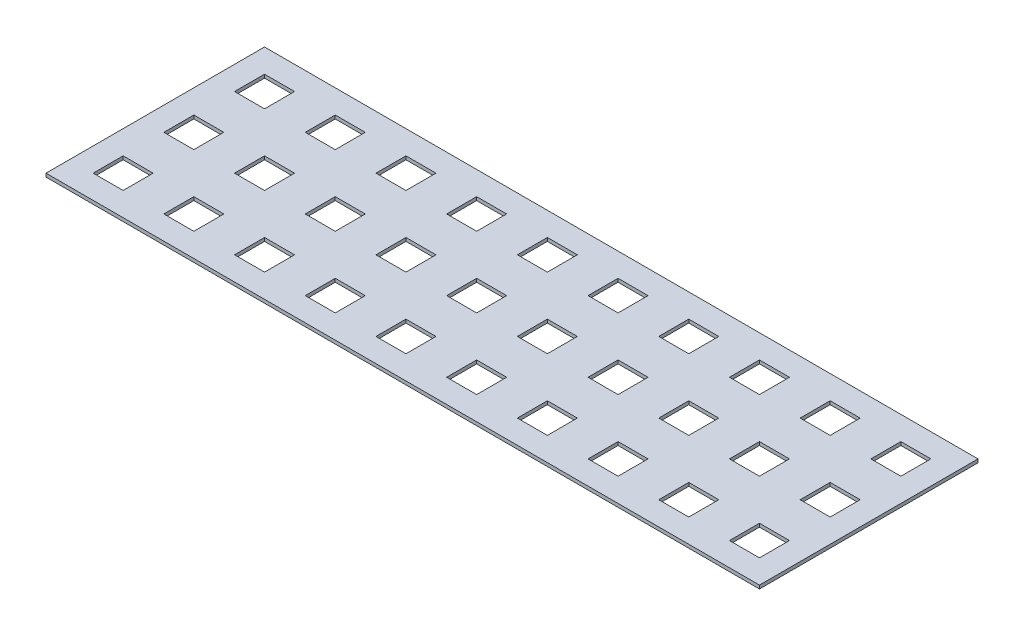
SolidWorks part; units mm, degrees
ref_plane "Ön Düzlem" through (0, 0, 0) normal (0, 0, 1) x (1, 0, 0)
ref_plane "Üst Düzlem" through (0, 0, 0) normal (0, 1, 0) x (1, 0, 0)
ref_plane "Sağ Düzlem" through (0, 0, 0) normal (1, 0, 0) x (0, 0, -1)
sketch "Çizim1" plane through (0, 0, 0) normal (0, 1, 0) x (1, 0, 0)
  line L0 (18, 49.5) -> (18, 34.5) construction
  line L1 (0, 0) -> (166.5, 0)
  line L2 (0, 0) -> (0, 51)
  line L3 (0, 51) -> (166.5, 51)
  line L4 (166.5, 0) -> (166.5, 51)
  line L5 (1.5, 49.5) -> (16.5, 49.5) construction
  line L6 (1.5, 49.5) -> (1.5, 34.5) construction
  line L7 (1.5, 34.5) -> (16.5, 34.5) construction
  line L8 (16.5, 49.5) -> (16.5, 34.5) construction
  line L9 (18, 49.5) -> (33, 49.5) construction
  line L10 (33, 49.5) -> (33, 34.5) construction
  line L11 (18, 34.5) -> (33, 34.5) construction
  line L12 (34.5, 49.5) -> (34.5, 34.5) construction
  line L13 (34.5, 49.5) -> (49.5, 49.5) construction
  line L14 (49.5, 49.5) -> (49.5, 34.5) construction
  line L15 (34.5, 34.5) -> (49.5, 34.5) construction
  line L16 (51, 49.5) -> (51, 34.5) construction
  line L17 (51, 49.5) -> (66, 49.5) construction
  line L18 (66, 49.5) -> (66, 34.5) construction
  line L19 (51, 34.5) -> (66, 34.5) construction
  line L20 (67.5, 49.5) -> (67.5, 34.5) construction
  line L21 (67.5, 49.5) -> (82.5, 49.5) construction
  line L22 (82.5, 49.5) -> (82.5, 34.5) construction
  line L23 (67.5, 34.5) -> (82.5, 34.5) construction
  line L24 (84, 49.5) -> (84, 34.5) construction
  line L25 (84, 49.5) -> (99, 49.5) construction
  line L26 (99, 49.5) -> (99, 34.5) construction
  line L27 (84, 34.5) -> (99, 34.5) construction
  line L28 (100.5, 49.5) -> (100.5, 34.5) construction
  line L29 (100.5, 49.5) -> (115.5, 49.5) construction
  line L30 (115.5, 49.5) -> (115.5, 34.5) construction
  line L31 (100.5, 34.5) -> (115.5, 34.5) construction
  line L32 (117, 49.5) -> (117, 34.5) construction
  line L33 (117, 49.5) -> (132, 49.5) construction
  line L34 (132, 49.5) -> (132, 34.5) construction
  line L35 (117, 34.5) -> (132, 34.5) construction
  line L36 (133.5, 49.5) -> (133.5, 34.5) construction
  line L37 (133.5, 49.5) -> (148.5, 49.5) construction
  line L38 (148.5, 49.5) -> (148.5, 34.5) construction
  line L39 (133.5, 34.5) -> (148.5, 34.5) construction
  line L40 (150, 49.5) -> (150, 34.5) construction
  line L41 (150, 49.5) -> (165, 49.5) construction
  line L42 (165, 49.5) -> (165, 34.5) construction
  line L43 (150, 34.5) -> (165, 34.5) construction
  line L44 (1.5, 33) -> (1.5, 18) construction
  line L45 (1.5, 33) -> (16.5, 33) construction
  line L46 (16.5, 33) -> (16.5, 18) construction
  line L47 (1.5, 18) -> (16.5, 18) construction
  line L48 (18, 33) -> (33, 33) construction
  line L49 (18, 33) -> (18, 18) construction
  line L50 (18, 18) -> (33, 18) construction
  line L51 (33, 33) -> (33, 18) construction
  line L52 (34.5, 33) -> (34.5, 18) construction
  line L53 (34.5, 33) -> (49.5, 33) construction
  line L54 (34.5, 18) -> (49.5, 18) construction
  line L55 (49.5, 33) -> (49.5, 18) construction
  line L56 (51, 33) -> (51, 18) construction
  line L57 (51, 33) -> (66, 33) construction
  line L58 (51, 18) -> (66, 18) construction
  line L59 (66, 33) -> (66, 18) construction
  line L60 (67.5, 33) -> (67.5, 18) construction
  line L61 (67.5, 33) -> (82.5, 33) construction
  line L62 (67.5, 18) -> (82.5, 18) construction
  line L63 (82.5, 33) -> (82.5, 18) construction
  line L64 (84, 33) -> (84, 18) construction
  line L65 (84, 33) -> (99, 33) construction
  line L66 (84, 18) -> (99, 18) construction
  line L67 (99, 33) -> (99, 18) construction
  line L68 (100.5, 33) -> (100.5, 18) construction
  line L69 (100.5, 18) -> (115.5, 18) construction
  line L70 (115.5, 33) -> (115.5, 18) construction
  line L71 (117, 33) -> (117, 18) construction
  line L72 (100.5, 33) -> (115.5, 33) construction
  line L73 (117, 33) -> (132, 33) construction
  line L74 (117, 18) -> (132, 18) construction
  line L75 (132, 33) -> (132, 18) construction
  line L76 (133.5, 33) -> (133.5, 18) construction
  line L77 (133.5, 18) -> (148.5, 18) construction
  line L78 (150, 18) -> (165, 18) construction
  line L79 (150, 33) -> (150, 18) construction
  line L80 (148.5, 33) -> (148.5, 18) construction
  line L81 (165, 33) -> (165, 18) construction
  line L82 (150, 33) -> (165, 33) construction
  line L83 (133.5, 33) -> (148.5, 33) construction
  line L84 (1.5, 16.5) -> (1.5, 1.5) construction
  line L85 (1.5, 16.5) -> (16.5, 16.5) construction
  line L86 (16.5, 16.5) -> (16.5, 1.5) construction
  line L87 (1.5, 1.5) -> (16.5, 1.5) construction
  line L88 (18, 16.5) -> (33, 16.5) construction
  line L89 (18, 16.5) -> (18, 1.5) construction
  line L90 (18, 1.5) -> (33, 1.5) construction
  line L91 (33, 16.5) -> (33, 1.5) construction
  line L92 (34.5, 16.5) -> (34.5, 1.5) construction
  line L93 (34.5, 16.5) -> (49.5, 16.5) construction
  line L94 (34.5, 1.5) -> (49.5, 1.5) construction
  line L95 (49.5, 16.5) -> (49.5, 1.5) construction
  line L96 (51, 16.5) -> (51, 1.5) construction
  line L97 (51, 16.5) -> (66, 16.5) construction
  line L98 (51, 1.5) -> (66, 1.5) construction
  line L99 (66, 16.5) -> (66, 1.5) construction
  line L100 (67.5, 16.5) -> (67.5, 1.5) construction
  line L101 (67.5, 16.5) -> (82.5, 16.5) construction
  line L102 (67.5, 1.5) -> (82.5, 1.5) construction
  line L103 (82.5, 16.5) -> (82.5, 1.5) construction
  line L104 (84, 16.5) -> (84, 1.5) construction
  line L105 (84, 16.5) -> (99, 16.5) construction
  line L106 (84, 1.5) -> (99, 1.5) construction
  line L107 (99, 16.5) -> (99, 1.5) construction
  line L108 (100.5, 16.5) -> (100.5, 1.5) construction
  line L109 (100.5, 1.5) -> (115.5, 1.5) construction
  line L110 (115.5, 16.5) -> (115.5, 1.5) construction
  line L111 (117, 16.5) -> (117, 1.5) construction
  line L112 (100.5, 16.5) -> (115.5, 16.5) construction
  line L113 (117, 16.5) -> (132, 16.5) construction
  line L114 (117, 1.5) -> (132, 1.5) construction
  line L115 (132, 16.5) -> (132, 1.5) construction
  line L116 (133.5, 16.5) -> (133.5, 1.5) construction
  line L117 (133.5, 1.5) -> (148.5, 1.5) construction
  line L118 (150, 1.5) -> (165, 1.5) construction
  line L119 (150, 16.5) -> (150, 1.5) construction
  line L120 (148.5, 16.5) -> (148.5, 1.5) construction
  line L121 (165, 16.5) -> (165, 1.5) construction
  line L122 (150, 16.5) -> (165, 16.5) construction
  line L123 (133.5, 16.5) -> (148.5, 16.5) construction
  line L124 (16.5, 49.5) -> (1.5, 34.5) construction
  line L125 (1.5, 49.5) -> (16.5, 34.5) construction
  line L126 (18, 49.5) -> (33, 34.5) construction
  line L127 (33, 49.5) -> (18, 34.5) construction
  line L128 (22, 45.5) -> (22, 38.5)
  line L129 (5.5, 45.5) -> (12.5, 45.5)
  line L130 (5.5, 45.5) -> (5.5, 38.5)
  line L131 (5.5, 38.5) -> (12.5, 38.5)
  line L132 (12.5, 45.5) -> (12.5, 38.5)
  line L133 (5.5, 45.5) -> (12.5, 38.5) construction
  line L134 (5.5, 38.5) -> (12.5, 45.5) construction
  line L135 (22, 45.5) -> (29, 45.5)
  line L136 (29, 45.5) -> (29, 38.5)
  line L137 (22, 38.5) -> (29, 38.5)
  line L138 (38.5, 45.5) -> (38.5, 38.5)
  line L139 (38.5, 45.5) -> (45.5, 45.5)
  line L140 (45.5, 45.5) -> (45.5, 38.5)
  line L141 (38.5, 38.5) -> (45.5, 38.5)
  line L142 (55, 45.5) -> (55, 38.5)
  line L143 (55, 45.5) -> (62, 45.5)
  line L144 (62, 45.5) -> (62, 38.5)
  line L145 (55, 38.5) -> (62, 38.5)
  line L146 (71.5, 45.5) -> (71.5, 38.5)
  line L147 (71.5, 45.5) -> (78.5, 45.5)
  line L148 (78.5, 45.5) -> (78.5, 38.5)
  line L149 (71.5, 38.5) -> (78.5, 38.5)
  line L150 (88, 45.5) -> (88, 38.5)
  line L151 (88, 45.5) -> (95, 45.5)
  line L152 (95, 45.5) -> (95, 38.5)
  line L153 (88, 38.5) -> (95, 38.5)
  line L154 (104.5, 45.5) -> (104.5, 38.5)
  line L155 (104.5, 45.5) -> (111.5, 45.5)
  line L156 (111.5, 45.5) -> (111.5, 38.5)
  line L157 (104.5, 38.5) -> (111.5, 38.5)
  line L158 (121, 45.5) -> (121, 38.5)
  line L159 (121, 45.5) -> (128, 45.5)
  line L160 (128, 45.5) -> (128, 38.5)
  line L161 (121, 38.5) -> (128, 38.5)
  line L162 (137.5, 45.5) -> (137.5, 38.5)
  line L163 (137.5, 45.5) -> (144.5, 45.5)
  line L164 (144.5, 45.5) -> (144.5, 38.5)
  line L165 (137.5, 38.5) -> (144.5, 38.5)
  line L166 (154, 45.5) -> (154, 38.5)
  line L167 (154, 45.5) -> (161, 45.5)
  line L168 (161, 45.5) -> (161, 38.5)
  line L169 (154, 38.5) -> (161, 38.5)
  line L170 (22, 29) -> (22, 22)
  line L171 (22, 29) -> (29, 29)
  line L172 (29, 29) -> (29, 22)
  line L173 (22, 22) -> (29, 22)
  line L174 (38.5, 29) -> (38.5, 22)
  line L175 (38.5, 29) -> (45.5, 29)
  line L176 (45.5, 29) -> (45.5, 22)
  line L177 (38.5, 22) -> (45.5, 22)
  line L178 (55, 29) -> (55, 22)
  line L179 (55, 29) -> (62, 29)
  line L180 (62, 29) -> (62, 22)
  line L181 (55, 22) -> (62, 22)
  line L182 (71.5, 29) -> (71.5, 22)
  line L183 (71.5, 29) -> (78.5, 29)
  line L184 (78.5, 29) -> (78.5, 22)
  line L185 (71.5, 22) -> (78.5, 22)
  line L186 (88, 29) -> (88, 22)
  line L187 (88, 29) -> (95, 29)
  line L188 (95, 29) -> (95, 22)
  line L189 (88, 22) -> (95, 22)
  line L190 (104.5, 29) -> (104.5, 22)
  line L191 (104.5, 29) -> (111.5, 29)
  line L192 (111.5, 29) -> (111.5, 22)
  line L193 (104.5, 22) -> (111.5, 22)
  line L194 (121, 29) -> (121, 22)
  line L195 (121, 29) -> (128, 29)
  line L196 (128, 29) -> (128, 22)
  line L197 (121, 22) -> (128, 22)
  line L198 (137.5, 29) -> (137.5, 22)
  line L199 (137.5, 29) -> (144.5, 29)
  line L200 (144.5, 29) -> (144.5, 22)
  line L201 (137.5, 22) -> (144.5, 22)
  line L202 (154, 29) -> (154, 22)
  line L203 (154, 29) -> (161, 29)
  line L204 (161, 29) -> (161, 22)
  line L205 (154, 22) -> (161, 22)
  line L206 (22, 12.5) -> (22, 5.5)
  line L207 (22, 12.5) -> (29, 12.5)
  line L208 (29, 12.5) -> (29, 5.5)
  line L209 (22, 5.5) -> (29, 5.5)
  line L210 (38.5, 12.5) -> (38.5, 5.5)
  line L211 (38.5, 12.5) -> (45.5, 12.5)
  line L212 (45.5, 12.5) -> (45.5, 5.5)
  line L213 (38.5, 5.5) -> (45.5, 5.5)
  line L214 (55, 12.5) -> (55, 5.5)
  line L215 (55, 12.5) -> (62, 12.5)
  line L216 (62, 12.5) -> (62, 5.5)
  line L217 (55, 5.5) -> (62, 5.5)
  line L218 (71.5, 12.5) -> (71.5, 5.5)
  line L219 (71.5, 12.5) -> (78.5, 12.5)
  line L220 (78.5, 12.5) -> (78.5, 5.5)
  line L221 (71.5, 5.5) -> (78.5, 5.5)
  line L222 (88, 12.5) -> (88, 5.5)
  line L223 (88, 12.5) -> (95, 12.5)
  line L224 (95, 12.5) -> (95, 5.5)
  line L225 (88, 5.5) -> (95, 5.5)
  line L226 (104.5, 12.5) -> (104.5, 5.5)
  line L227 (104.5, 12.5) -> (111.5, 12.5)
  line L228 (111.5, 12.5) -> (111.5, 5.5)
  line L229 (104.5, 5.5) -> (111.5, 5.5)
  line L230 (121, 12.5) -> (121, 5.5)
  line L231 (121, 12.5) -> (128, 12.5)
  line L232 (128, 12.5) -> (128, 5.5)
  line L233 (121, 5.5) -> (128, 5.5)
  line L234 (137.5, 12.5) -> (137.5, 5.5)
  line L235 (137.5, 12.5) -> (144.5, 12.5)
  line L236 (144.5, 12.5) -> (144.5, 5.5)
  line L237 (137.5, 5.5) -> (144.5, 5.5)
  line L238 (154, 12.5) -> (154, 5.5)
  line L239 (154, 12.5) -> (161, 12.5)
  line L240 (161, 12.5) -> (161, 5.5)
  line L241 (154, 5.5) -> (161, 5.5)
  line L242 (5.5, 29) -> (5.5, 22)
  line L243 (5.5, 29) -> (12.5, 29)
  line L244 (12.5, 29) -> (12.5, 22)
  line L245 (5.5, 22) -> (12.5, 22)
  line L246 (5.5, 12.5) -> (5.5, 5.5)
  line L247 (5.5, 12.5) -> (12.5, 12.5)
  line L248 (12.5, 12.5) -> (12.5, 5.5)
  line L249 (5.5, 5.5) -> (12.5, 5.5)
  point P9 (9, 42)
  dimension "D1" = 166.5
  dimension "D2" = 51
  dimension "D3" = 15
  dimension "D4" = 15
  dimension "D5" = 1.5
  dimension "D6" = 1.5
  dimension "D9" = 7
  dimension "D10" = 7
  dimension "D7" = 10
  dimension "D8" = 3
  dimension "D11" = 10
  dimension "D12" = 3
extrude "Yükseklik-Ekstrüzyon1" add sketch "Çizim1" along normal blind 0.8
